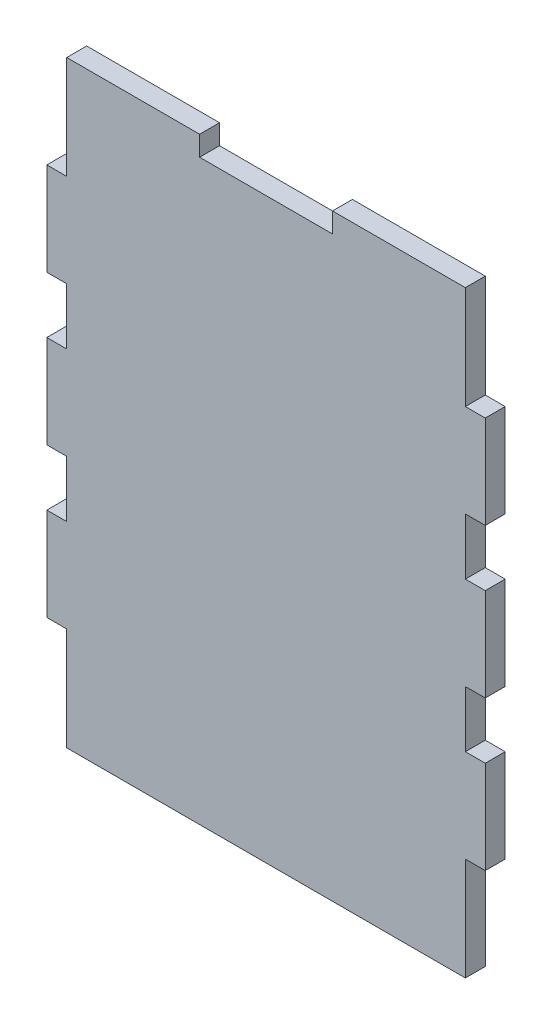
SolidWorks part; units mm, degrees
material "ABS"
ref_plane "Plan de face" through (0, 0, 0) normal (0, 0, 1) x (1, 0, 0)
ref_plane "Plan de dessus" through (0, 0, 0) normal (0, 1, 0) x (1, 0, 0)
ref_plane "Plan de droite" through (0, 0, 0) normal (1, 0, 0) x (0, 0, -1)
sketch "Esquisse1" plane through (0, 0, 0) normal (0, 0, 1) x (1, 0, 0)
  line L0 (-30, 0) -> (30, 0) construction
  line L1 (30, -45) -> (-30, -45)
  line L2 (30, -45) -> (30, 45)
  line L3 (30, 45) -> (-30, 45)
  line L4 (-30, -45) -> (-30, 45)
  line L5 (30, -45) -> (-30, 45) construction
  line L6 (30, 45) -> (-30, -45) construction
  line L7 (-30, 22.5) -> (30, 22.5) construction
  line L8 (-30, -22.5) -> (30, -22.5) construction
  line L10 (-27, 15.5) -> (-33, 15.5)
  line L11 (-27, 15.5) -> (-27, 29.5)
  line L12 (-27, 29.5) -> (-33, 29.5)
  line L13 (-33, 15.5) -> (-33, 29.5)
  line L14 (-27, 15.5) -> (-33, 29.5) construction
  line L15 (-27, 29.5) -> (-33, 15.5) construction
  line L16 (-27, -7) -> (-33, -7)
  line L17 (-27, -7) -> (-27, 7)
  line L18 (-27, 7) -> (-33, 7)
  line L19 (-33, -7) -> (-33, 7)
  line L20 (-27, -7) -> (-33, 7) construction
  line L21 (-27, 7) -> (-33, -7) construction
  line L22 (-27, -29.5) -> (-33, -29.5)
  line L23 (-27, -29.5) -> (-27, -15.5)
  line L24 (-27, -15.5) -> (-33, -15.5)
  line L25 (-33, -29.5) -> (-33, -15.5)
  line L26 (-27, -29.5) -> (-33, -15.5) construction
  line L27 (-27, -15.5) -> (-33, -29.5) construction
  line L28 (33, -29.5) -> (27, -29.5)
  line L29 (33, -29.5) -> (33, -15.5)
  line L30 (33, -15.5) -> (27, -15.5)
  line L31 (27, -29.5) -> (27, -15.5)
  line L32 (33, -29.5) -> (27, -15.5) construction
  line L33 (33, -15.5) -> (27, -29.5) construction
  line L34 (33, -7) -> (27, -7)
  line L35 (33, -7) -> (33, 7)
  line L36 (33, 7) -> (27, 7)
  line L37 (27, -7) -> (27, 7)
  line L38 (33, -7) -> (27, 7) construction
  line L39 (33, 7) -> (27, -7) construction
  line L40 (33, 15.5) -> (27, 15.5)
  line L41 (33, 15.5) -> (33, 29.5)
  line L42 (33, 29.5) -> (27, 29.5)
  line L43 (27, 15.5) -> (27, 29.5)
  line L44 (33, 15.5) -> (27, 29.5) construction
  line L45 (33, 29.5) -> (27, 15.5) construction
  point P0 (0, 0)
  point P36 (25, -22.5)
  dimension "D1" = 90
  dimension "D2" = 60
  dimension "D3" = 45
  dimension "D4" = 22.5
  dimension "D5" = 6
  dimension "D6" = 14
extrude "Boss.-Extru.1" add sketch "Esquisse1" along normal blind 3 contours L40 L43 L42 L2 L3 L4 L12 L11 L10 L18 L17 L16 L24 L23 L22 L1 L28 L31 L30 L34 L37 L36 | L29 L30 L2 L28 | L35 L36 L2 L34 | L41 L42 L2 L40
sketch "Esquisse2" plane through (0, 0, 3) normal (0, 0, 1) x (1, 0, 0)
  line L0 (30, 45) -> (-30, 45) construction
  line L1 (10, 42) -> (-10, 42)
  line L2 (10, 42) -> (10, 48)
  line L3 (10, 48) -> (-10, 48)
  line L4 (-10, 42) -> (-10, 48)
  line L5 (10, 42) -> (-10, 48) construction
  line L6 (10, 48) -> (-10, 42) construction
  point P0 (0, 45)
  dimension "D1" = 6
  dimension "D2" = 20
extrude "Enlèv. mat.-Extru.1" cut sketch "Esquisse2" against normal blind 10
